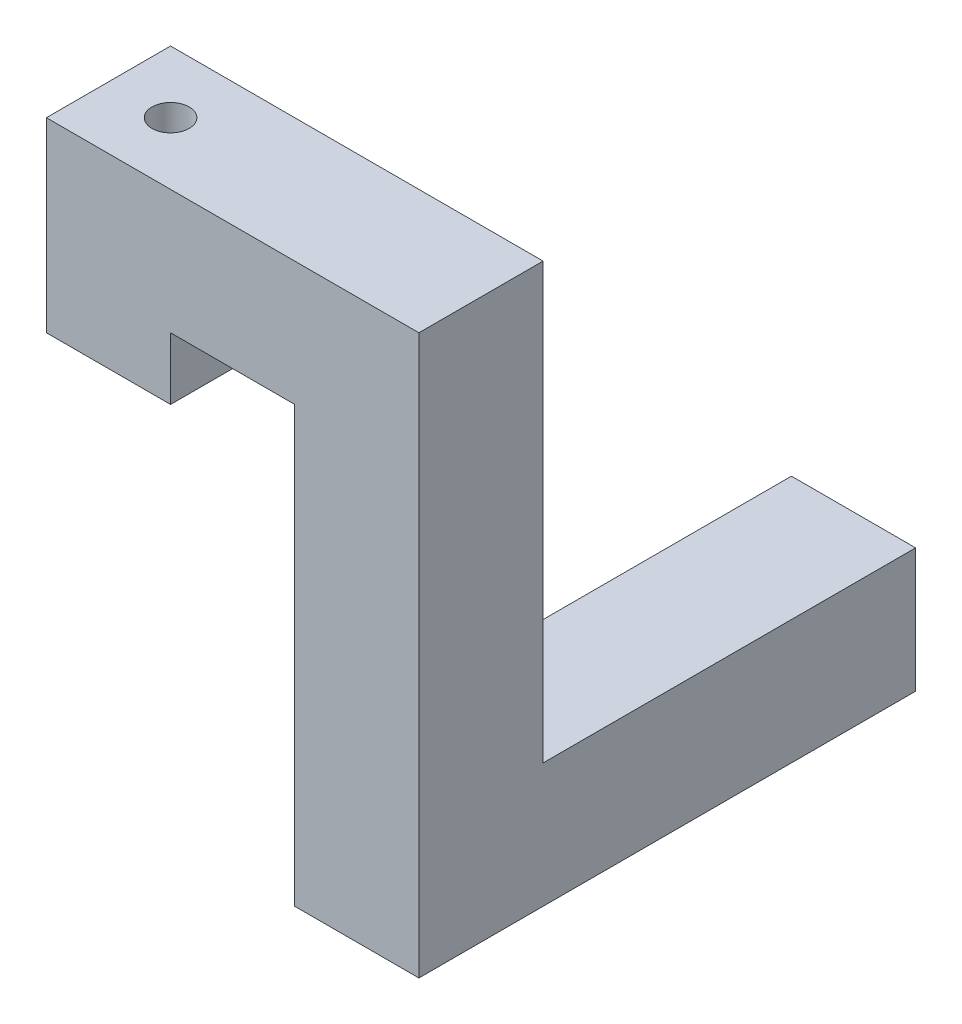
SolidWorks part; units mm, degrees
ref_plane "前视基准面" through (0, 0, 0) normal (0, 0, 1) x (1, 0, 0)
ref_plane "上视基准面" through (0, 0, 0) normal (0, 1, 0) x (1, 0, 0)
ref_plane "右视基准面" through (0, 0, 0) normal (1, 0, 0) x (0, 0, -1)
other "Configuration Table"
sketch "草图1" plane through (0, 0, 0) normal (0, 1, 0) x (1, 0, 0)
  line L1 (-10, 10) -> (10, 10)
  line L2 (-10, 10) -> (-10, -10)
  line L3 (-10, -10) -> (10, -10)
  line L4 (10, 10) -> (10, -10)
  line L5 (-10, 10) -> (10, -10) construction
  line L6 (-10, -10) -> (10, 10) construction
  point P0 (0, 0)
  dimension "D1" = 20
  dimension "D2" = 20
extrude "凸台-拉伸1" add sketch "草图1" along normal blind 30
sketch "草图2" plane through (10, 0, 0) normal (1, 0, 0) x (0, 0, -1)
  line L0 (10, 30) -> (10, 0) construction
  line L1 (-10, 30) -> (10, 30)
  line L2 (-10, 30) -> (-10, 10)
  line L3 (-10, 10) -> (10, 10)
  line L4 (10, 30) -> (10, 10)
  dimension "D1" = 20
  dimension "D2" = 20
extrude "凸台-拉伸2" add sketch "草图2" along normal blind 40 contours L2 L1 L4 L3
sketch "草图6" plane through (0, 10, 0) normal (0, -1, 0) x (1, 0, 0)
  line L1 (50, -10) -> (10, -10) construction
  line L2 (50, 10) -> (30, 10)
  line L3 (50, 10) -> (50, -10)
  line L4 (50, -10) -> (30, -10)
  line L5 (30, 10) -> (30, -10)
extrude "凸台-拉伸3" add sketch "草图6" along normal blind 70 contours L3 L2 L5 L4
sketch "草图7" plane through (0, 0, -10) normal (0, 0, -1) x (-1, 0, 0)
  line L0 (-50, 30) -> (-50, -60) construction
  line L1 (-30, -60) -> (-50, -60)
  line L2 (-30, -60) -> (-30, -40)
  line L3 (-30, -40) -> (-50, -40)
  line L4 (-50, -60) -> (-50, -40)
extrude "凸台-拉伸4" add sketch "草图7" along normal blind 60
sketch "草图8" plane through (0, 0, 0) normal (0, -1, 0) x (-1, 0, 0)
  circle A0 centre (0, 0) radius 3
  dimension "D1" = 6
extrude "切除-拉伸1" cut sketch "草图8" against normal blind 60
sketch3d "3D草图4" plane through (0, 0, 0) normal (0, 0, 1) x (1, 0, 0)
